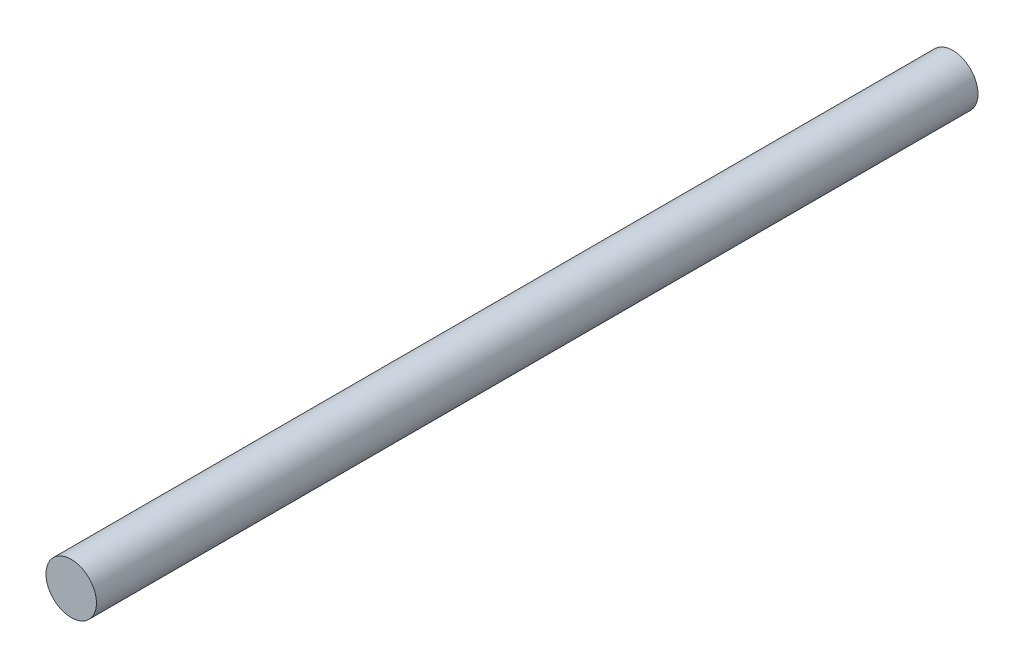
SolidWorks part; units mm, degrees
material "Plain Carbon Steel"
ref_plane "Front Plane" through (0, 0, 0) normal (0, 0, 1) x (1, 0, 0)
ref_plane "Top Plane" through (0, 0, 0) normal (0, 1, 0) x (1, 0, 0)
ref_plane "Right Plane" through (0, 0, 0) normal (1, 0, 0) x (0, 0, -1)
sketch "Sketch1" plane through (0, 0, 0) normal (0, 0, 1) x (1, 0, 0)
  circle A0 centre (0, 0) radius 4
  dimension "D1" = 8
extrude "Boss-Extrude1" add sketch "Sketch1" along normal blind 139.7
